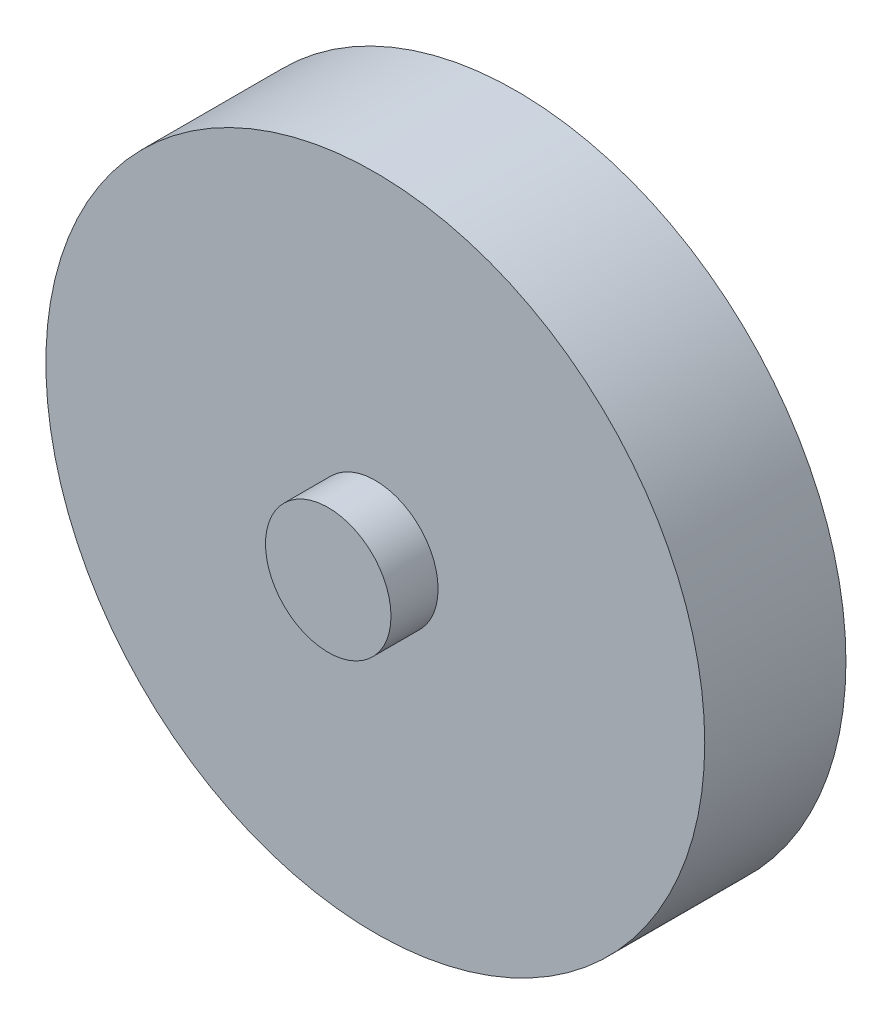
SolidWorks part; units mm, degrees
ref_plane "前视基准面" through (0, 0, 0) normal (0, 0, 1) x (1, 0, 0)
ref_plane "上视基准面" through (0, 0, 0) normal (0, 1, 0) x (1, 0, 0)
ref_plane "右视基准面" through (0, 0, 0) normal (1, 0, 0) x (0, 0, -1)
other "Configuration Table"
sketch "草图1" plane through (0, 0, 0) normal (0, 0, 1) x (1, 0, 0)
  circle A0 centre (0, 0) radius 8
extrude "凸台-拉伸1" add sketch "草图1" along normal blind 24
sketch "草图2" plane through (0, 0, 0) normal (0, 0, 1) x (1, 0, 0)
  circle A0 centre (0, 0) radius 42
extrude "凸台-拉伸2" add sketch "草图2" along normal blind 18
sketch "草图3" plane through (0, 0, 18) normal (0, 0, 1) x (1, 0, 0)
  line L0 (37.445, 2.0305) -> (37.5326, 2.0353)
  line L1 (37.5326, 2.0353) -> (37.6055, 2.0362)
  line L2 (37.6055, 2.0362) -> (37.824, 2.0269)
  line L3 (37.824, 2.0269) -> (38.1865, 1.9892)
  line L4 (38.1865, 1.9892) -> (38.6899, 1.9052)
  line L5 (38.6899, 1.9052) -> (39.3292, 1.7573)
  line L6 (39.3292, 1.7573) -> (40.0978, 1.5285)
  line L7 (40.0978, 1.5285) -> (40.9876, 1.5285)
  line L8 (40.9876, 1.5285) -> (42, 0)
  line L9 (41.4938, 0.7643) -> (42, 1.5285)
  line L10 (42, 1.5285) -> (42, 3.2953)
  line L11 (42, 3.2953) -> (42, 4.5468)
  line L12 (42, 4.5468) -> (41.5984, 5.7942)
  line L13 (41.5984, 5.7942) -> (40.0978, 5.7942)
  line L14 (40.0978, 5.7942) -> (40.0978, 4.5468)
  line L15 (40.0978, 4.5468) -> (38.6899, 4.5468)
  line L16 (38.6899, 4.5468) -> (38.5116, 4.1707)
  line L17 (38.5116, 4.1707) -> (38.0276, 4.009)
  line L18 (38.0276, 4.009) -> (37.6754, 3.9151)
  line L19 (37.6754, 3.9151) -> (37.461, 3.8716)
  line L20 (37.461, 3.8716) -> (37.3889, 3.8612)
  line L21 (37.3889, 3.8612) -> (37.3016, 3.8521)
  line L22 (37.3016, 3.8521) -> (37.3458, 3.3974)
  line L23 (37.3458, 3.3974) -> (37.3844, 2.9422)
  line L24 (37.3844, 2.9422) -> (37.445, 2.0305)
  circle A0 centre (0, 0) radius 42 construction
